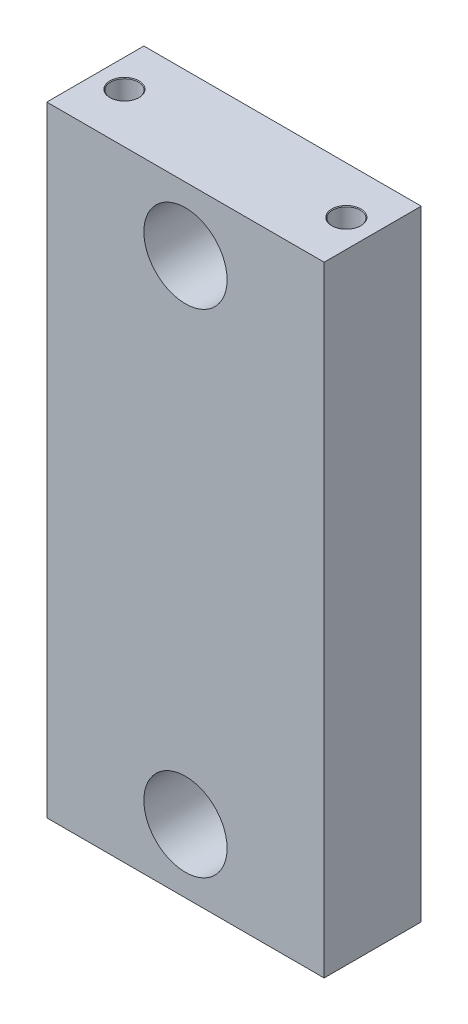
SolidWorks part; units mm, degrees
ref_plane "Front Plane" through (0, 0, 0) normal (0, 0, 1) x (1, 0, 0)
ref_plane "Top Plane" through (0, 0, 0) normal (0, 1, 0) x (1, 0, 0)
ref_plane "Right Plane" through (0, 0, 0) normal (1, 0, 0) x (0, 0, -1)
sketch "Sketch2" plane through (0, 0, 0) normal (0, 0, 1) x (1, 0, 0)
  line L8 (-5, -27.35) -> (5, -27.35)
  line L9 (-5, -27.35) -> (-5, -5)
  line L10 (-5, -5) -> (5, -5)
  line L11 (5, -27.35) -> (5, -5)
  line L12 (-5, -27.35) -> (5, -5) construction
  line L13 (-5, -5) -> (5, -27.35) construction
  circle A9 centre (0, -7.3) radius 1.5
  circle A10 centre (0, -25.05) radius 1.5
  point P0 (0, 0)
  point P8 (0, -16.175)
  dimension "D2" = 5
  dimension "D4" = 3
  dimension "D11" = 3
  dimension "D12" = 17.75
  dimension "D6" = 22.35
  dimension "D7" = 10
extrude "Boss-Extrude1" add sketch "Sketch2" along normal blind 3.5
sketch3d "3DSketch2" plane through (0, 0, 0) normal (0, 0, 1) x (1, 0, 0)
sketch "Sketch8" plane through (0, -5, 0) normal (0, 1, 0) x (1, 0, 0)
  line L0 (-4, -1.7) -> (4, -1.7) construction
  line L1 (-4, -0.9) -> (4, -0.9)
  line L2 (-4, -2.5) -> (4, -2.5)
  line L3 (-5, -3.5) -> (-5, 0) construction
  line L5 (-5, 0) -> (5, 0) construction
  arc A0 (-4, -0.9) -> (-4, -2.5) centre (-4, -1.7) ccw
  arc A1 (4, -2.5) -> (4, -0.9) centre (4, -1.7) ccw
  point P2 (0, -1.7)
  dimension "D1" = 8
  dimension "D2" = 1
  dimension "D3" = 0.8
  dimension "D4" = 0.9
hole_wizard "Ø1.0mm Dowel Hole1" positions "3DSketch5" profile "Sketch9" hole size "Ø1.0" standard "ANSI Metric"
sketch3d "3DSketch5"
  point P0 (-4, -5, 1.7)
  point P3 (4, -5, 1.7)
sketch "Sketch9" plane through (-4, -5, 1.7) normal (1, 0, 0) x (0, 0, 1)
  line L0 (0, 0) -> (0, 3.3004)
  line L1 (0, 3.3004) -> (0.5, 3)
  line L2 (0.5, 3) -> (0.5, 0.025)
  line L3 (0.5, 0.025) -> (0.525, 0)
  line L5 (0.525, 0) -> (0, 0)
  line L6 (-0.5, 0.025) -> (-0.525, 0) construction
  line L10 (0, 3.3004) -> (-0.5, 3) construction
  line L11 (0, -6.35) -> (0, 107.95) construction
  dimension "Hole Dia." = 1
  dimension "Hole Depth" = 3
  dimension "Near C'Sink Dia." = 1.05
  dimension "Near C'Sink Angle" = 90
  dimension "Drill Angle" = 118
